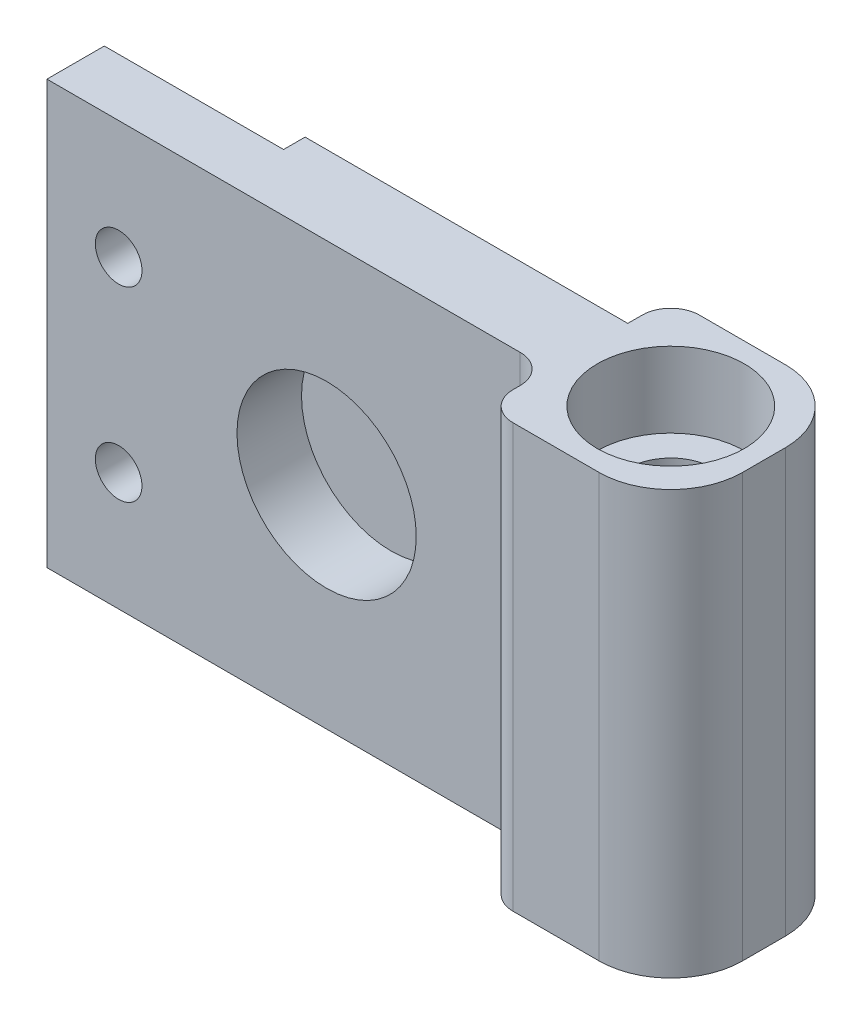
SolidWorks part; units mm, degrees
ref_plane "Ebene vorne" through (0, 0, 0) normal (0, 0, 1) x (1, 0, 0)
ref_plane "Ebene oben" through (0, 0, 0) normal (0, 1, 0) x (1, 0, 0)
ref_plane "Ebene rechts" through (0, 0, 0) normal (1, 0, 0) x (0, 0, -1)
sketch "Sketch1" plane through (0, 0, 0) normal (0, 1, 0) x (1, 0, 0)
  line L1 (6.5, -6.5) -> (-6.5, -6.5)
  line L2 (6.5, -6.5) -> (6.5, 6.5)
  line L3 (6.5, 6.5) -> (-6.5, 6.5)
  line L4 (-6.5, -6.5) -> (-6.5, 6.5)
  line L5 (6.5, -6.5) -> (-6.5, 6.5) construction
  line L6 (6.5, 6.5) -> (-6.5, -6.5) construction
  point P0 (0, 0)
  dimension "D1" = 13
  dimension "D2" = 13
extrude "Ball Bearing Block" add sketch "Sketch1" along normal blind 29.5
sketch "Sketch2" plane through (0, 0, 0) normal (0, -1, 0) x (1, 0, 0)
  line L0 (-41.5, 0) -> (-30.5906, 0) construction
  line L1 (-6.5, -2) -> (-41.5, -2)
  line L2 (-6.5, -2) -> (-6.5, 2)
  line L3 (-6.5, 2) -> (-41.5, 2)
  line L4 (-41.5, -2) -> (-41.5, 2)
  line L5 (-6.5, 0) -> (-18.074, 0) construction
  line L6 (-6.5, -6.5) -> (-6.5, 6.5) construction
  dimension "D1" = 4
  dimension "D2" = 35
extrude "Paddle Plate" add sketch "Sketch2" against normal up to surface (29.5 mm away) up to face at (0, 29.5, 0)
sketch "Sketch3" plane through (0, 29.5, 0) normal (0, 1, 0) x (1, 0, 0)
  circle A0 centre (0, 0) radius 5.125
  dimension "D1" = 10.25
extrude "Ballbearing 1" cut sketch "Sketch3" against normal blind 5.25
sketch "Sketch4" plane through (0, 0, 0) normal (0, -1, 0) x (1, 0, 0)
  circle A0 centre (0, 0) radius 5.125
  circle A1 centre (0, 0) radius 5.125 construction
extrude "Ballbearing 2" cut sketch "Sketch4" against normal blind 5
sketch "Sketch5" plane through (0, 24.25, 0) normal (0, 1, 0) x (1, 0, 0)
  circle A0 centre (0, 0) radius 3
  dimension "D1" = 6
extrude "Achse" cut sketch "Sketch5" against normal up to surface (19.25 mm away) up to face at (0, 5, -5.125)
fillet "Fillet1" radius 5 1 edges at (6.5, 14.75, -6.5)
fillet "Fillet2" radius 5 1 edges at (6.5, 14.75, 6.5)
fillet "Fillet3" radius 2 3 edges at (-6.5, 14.75, -6.5)
fillet "Fillet4" radius 2 1 edges at (-6.5, 14.75, 6.5)
fillet "Fillet7" radius 2 5 edges
sketch "Sketch6" plane through (0, 0, -2) normal (0, 0, -1) x (-1, 0, 0)
  line L0 (41.5, 14.75) -> (23.4297, 14.75) construction
  line L1 (41.5, 29.5) -> (41.5, 0) construction
  circle A0 centre (36.5, 8.25) radius 1.625
  circle A1 centre (36.5, 21.25) radius 1.625
  dimension "D1" = 3.25
  dimension "D2" = 6.5
  dimension "D3" = 5
extrude "M3 Paddle Screws" cut sketch "Sketch6" against normal up to surface (4 mm away) up to face at (-16.75, 14.75, 2)
sketch "Sketch8" plane through (0, 0, -2) normal (0, 0, -1) x (-1, 0, 0)
  line L0 (41.5, 0) -> (6.5, 0) construction
  line L1 (29, 0) -> (6.5, 0)
  line L2 (29, 0) -> (29, 29.5)
  line L3 (29, 29.5) -> (6.5, 29.5)
  line L4 (6.5, 0) -> (6.5, 29.5)
  line L5 (41.5, 29.5) -> (6.5, 29.5) construction
  line L6 (41.5, 29.5) -> (41.5, 0) construction
  line L7 (6.5, 29.5) -> (6.5, 0) construction
  dimension "D2" = 12.5
extrude "Top Plate" add sketch "Sketch8" along normal blind 1.5
sketch "Sketch7" plane through (0, 0, 2) normal (0, 0, -1) x (-1, 0, 0)
  line L0 (41.5, 14.75) -> (26.7911, 14.75) construction
  line L1 (41.5, 29.5) -> (41.5, 0) construction
  circle A0 centre (22, 14.75) radius 6.25
  dimension "D1" = 12.5
  dimension "D2" = 19
extrude "Magnet Pocket" cut sketch "Sketch7" along normal offset from surface (4.5 mm away) 1 up to face at (-17.75, 14.75, -3.5)
